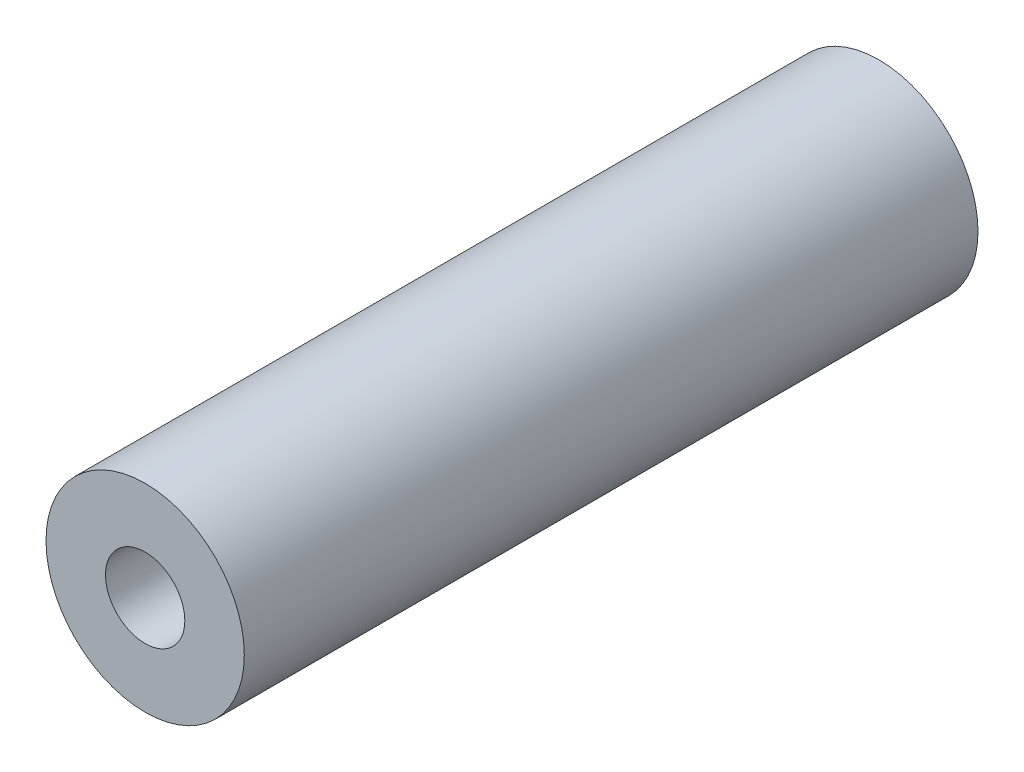
SolidWorks part; units mm, degrees
material "1060 합금"
ref_plane "정면" through (0, 0, 0) normal (0, 0, 1) x (1, 0, 0)
ref_plane "윗면" through (0, 0, 0) normal (0, 1, 0) x (1, 0, 0)
ref_plane "우측면" through (0, 0, 0) normal (1, 0, 0) x (0, 0, -1)
sketch "스케치1" plane through (0, 0, 0) normal (0, 0, 1) x (1, 0, 0)
  circle A0 centre (0, 0) radius 5
  dimension "D1" = 10
extrude "보스-돌출1" add sketch "스케치1" along normal blind 37
sketch "스케치2" plane through (0, 0, 37) normal (0, 0, 1) x (1, 0, 0)
  circle A0 centre (0, 0) radius 2
  dimension "D1" = 4
extrude "컷-돌출1" cut sketch "스케치2" against normal blind 15
sketch "스케치3" plane through (0, 0, 0) normal (0, 0, -1) x (-1, 0, 0)
  circle A0 centre (0, 0) radius 2
  dimension "D1" = 4
extrude "컷-돌출2" cut sketch "스케치3" against normal blind 15
